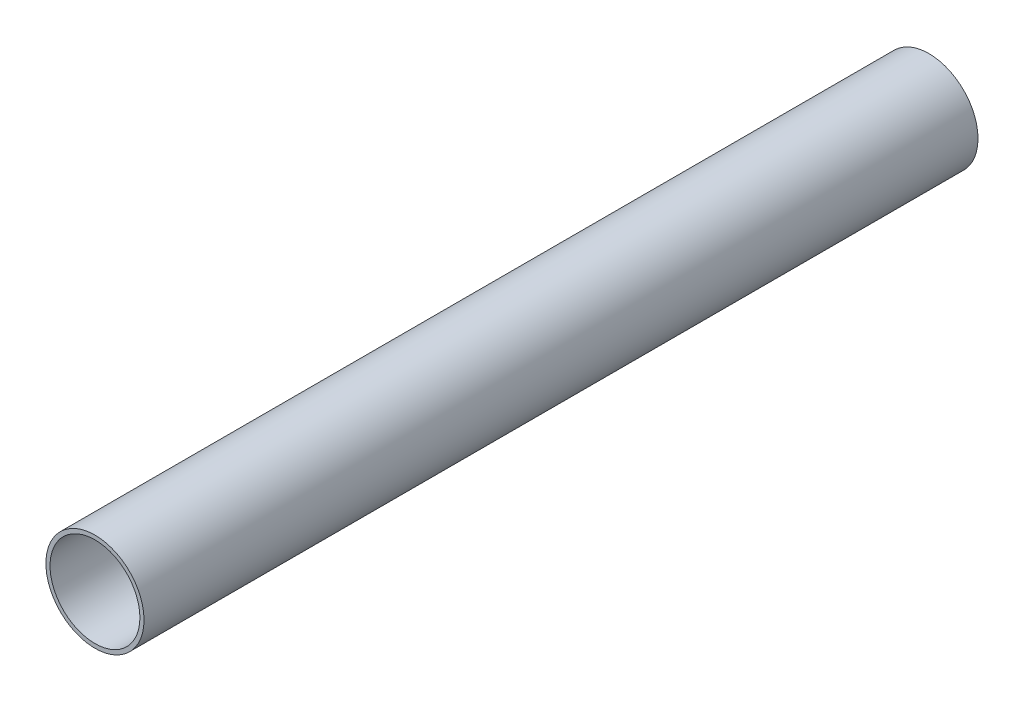
SolidWorks part; units mm, degrees
ref_plane "Front Plane" through (0, 0, 0) normal (0, 0, 1) x (1, 0, 0)
ref_plane "Top Plane" through (0, 0, 0) normal (0, 1, 0) x (1, 0, 0)
ref_plane "Right Plane" through (0, 0, 0) normal (1, 0, 0) x (0, 0, -1)
sketch "Sketch1" plane through (0, 0, 0) normal (0, 1, 0) x (1, 0, 0)
  line L2 (12.7, 0) -> (12.7, -215.9)
  line L3 (12.7, -215.9) -> (11.6332, -215.9)
  line L4 (11.6332, -215.9) -> (11.6332, 0)
  line L8 (0, 0) -> (0, 39700.89) construction
  line L9 (11.6332, 0) -> (12.7, 0)
  point P0 (0, 0)
  dimension "D1" = 215.9
  dimension "D2" = 25.4
  dimension "D3" = 1.0668
revolve "Revolve1" add sketch "Sketch1" angle 360 about L8
